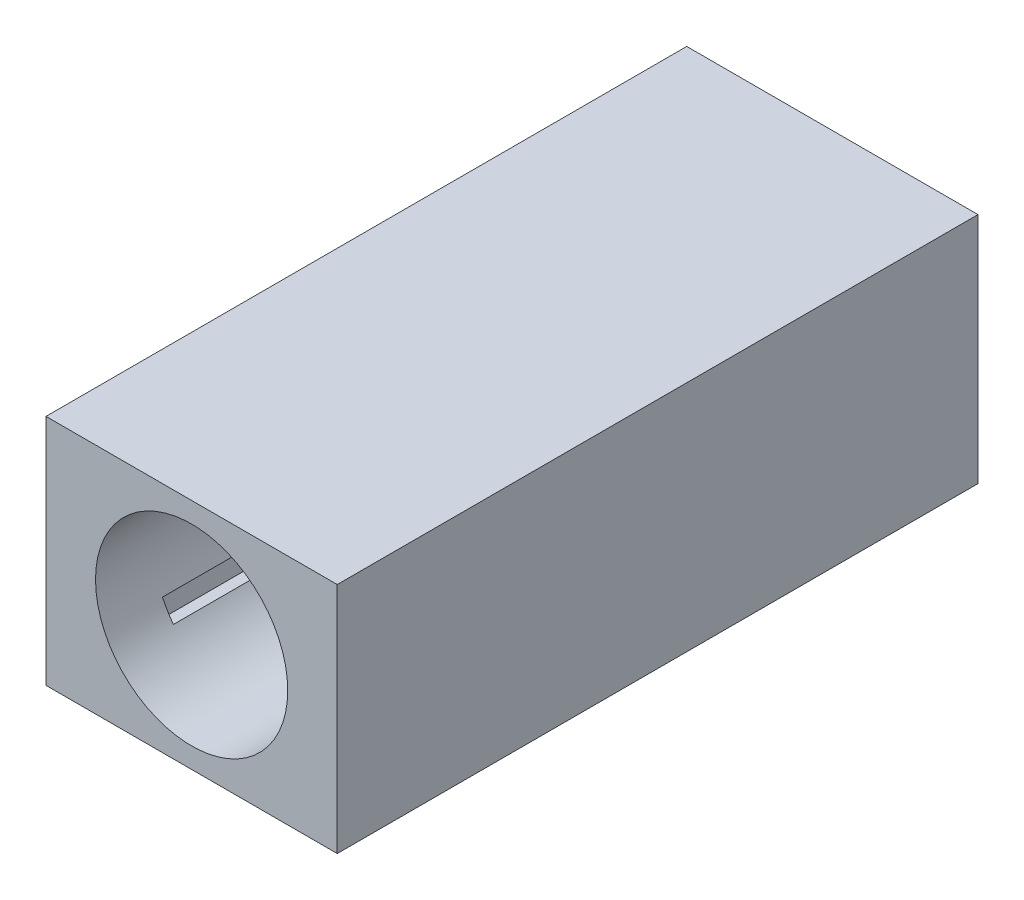
SolidWorks part; units mm, degrees
ref_plane "Front Plane" through (0, 0, 0) normal (0, 0, 1) x (1, 0, 0)
ref_plane "Top Plane" through (0, 0, 0) normal (0, 1, 0) x (1, 0, 0)
ref_plane "Right Plane" through (0, 0, 0) normal (1, 0, 0) x (0, 0, -1)
sketch "Sketch1" plane through (0, 0, 0) normal (0, 0, 1) x (1, 0, 0)
  line L0 (-2.5, 2) -> (-2.5, -2)
  line L1 (-2.5, -2) -> (2.5, -2)
  line L2 (2.5, -2) -> (2.5, 2)
  line L3 (2.5, 2) -> (-2.5, 2)
  line L4 (-2.5, -2) -> (2.5, 2) construction
  line L5 (-2.5, 2) -> (2.5, -2) construction
  line L6 (1.5, 1) -> (-1.5, 1)
  line L7 (-1.5, 1) -> (-1.5, -1)
  line L8 (-1.5, -1) -> (1.5, -1)
  line L9 (1.5, -1) -> (1.5, 1)
  point P2 (0, 0)
  dimension "D1" = 4
  dimension "D2" = 5
  dimension "D3" = 0
  dimension "D4" = 1
extrude "Boss-Extrude1" add sketch "Sketch1" along normal blind 10
sketch "Sketch2" plane through (0, 0, 10) normal (0, 0, 1) x (1, 0, 0)
  line L0 (2.5, 2) -> (-2.5, 2) construction
  line L1 (-2.5, 2) -> (2.5, 2)
  line L2 (-2.5, 2) -> (-2.5, -2)
  line L3 (-2.5, -2) -> (2.5, -2)
  line L4 (2.5, 2) -> (2.5, -2)
  line L5 (-2.5, 2) -> (-2.5, -2) construction
  circle A0 centre (0, 0) radius 1.65
  dimension "D1" = 3.3
extrude "Boss-Extrude2" add sketch "Sketch2" along normal blind 1
sketch "Sketch3" plane through (0, 0, 11) normal (0, 0, 1) x (1, 0, 0)
  circle A0 centre (0, 0) radius 1.65
extrude "Cut-Extrude1" cut sketch "Sketch3" against normal through all
